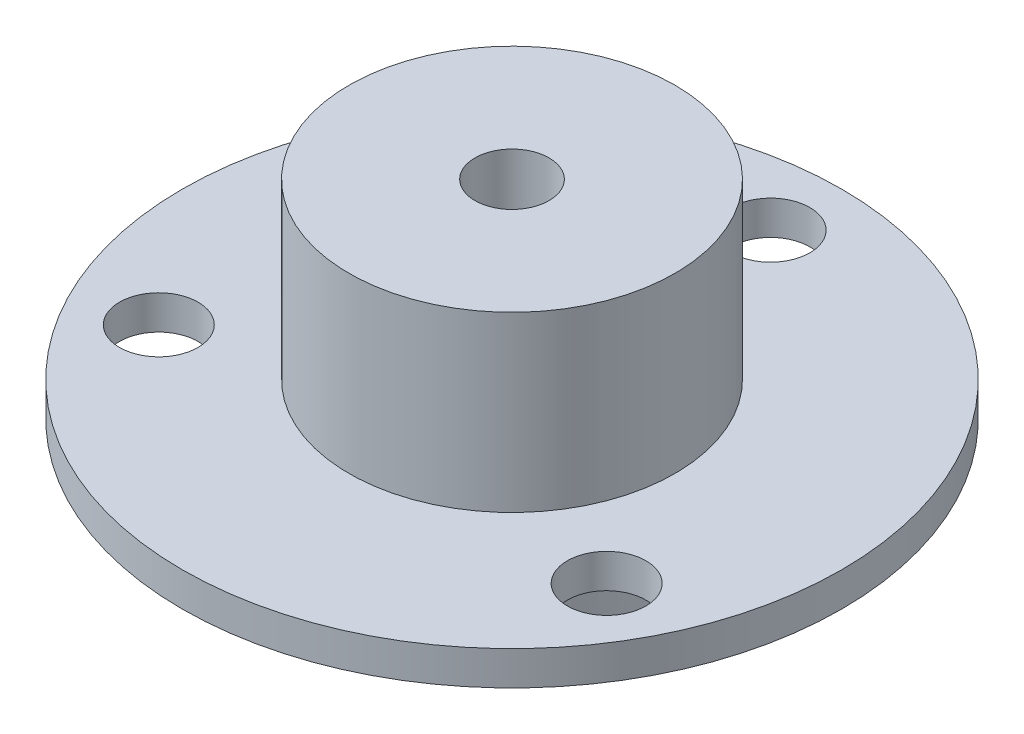
SolidWorks part; units mm, degrees
ref_plane "Front Plane" through (0, 0, 0) normal (0, 0, 1) x (1, 0, 0)
ref_plane "Top Plane" through (0, 0, 0) normal (0, 1, 0) x (1, 0, 0)
ref_plane "Right Plane" through (0, 0, 0) normal (1, 0, 0) x (0, 0, -1)
sketch "Sketch1" plane through (0, 0, 0) normal (0, 0, 1) x (1, 0, 0)
  line L0 (0, 19) -> (-11, 19)
  line L1 (-11, 19) -> (-11, 7.3)
  line L2 (-11, 7.3) -> (-22.25, 7.3)
  line L3 (-22.25, 7.3) -> (-22.25, 5)
  line L4 (-22.25, 5) -> (-11, 5)
  line L5 (-11, 5) -> (-11, 0)
  line L6 (-11, 0) -> (0, 0)
  line L7 (0, 0) -> (0, 19) construction
  line L8 (-2.5, 19) -> (-2.5, 0)
  point P10 (0, 0)
  dimension "D1" = 11
  dimension "D2" = 2.3
  dimension "D3" = 22.25
  dimension "D4" = 19
  dimension "D5" = 5
  dimension "D6" = 2.5
revolve "Revolve1" add sketch "Sketch1" angle 360 about L7
sketch "Sketch2" plane through (0, 7.3, 0) normal (0, 1, 0) x (1, 0, 0)
  circle A0 centre (0, 17.45) radius 2.65
  circle A1 centre (0, 0) radius 17.45 construction
  circle A2 centre (15.1121, -8.725) radius 2.65
  circle A3 centre (-15.1121, -8.725) radius 2.65
  point P6 (-38.3507, -11.7684)
  point P7 (0, 0)
  point P11 (0, 0)
  dimension "D1" = 5.3
  dimension "D2" = 34.9
  dimension "D3" = 3
extrude "Cut-Extrude1" cut sketch "Sketch2" against normal through all
